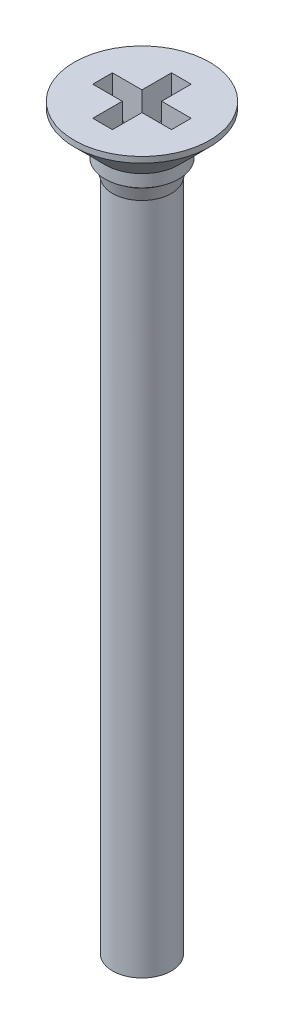
SolidWorks part; units mm, degrees
ref_plane "Vorderseite" through (0, 0, 0) normal (0, 0, 1) x (1, 0, 0)
ref_plane "Oben" through (0, 0, 0) normal (0, 1, 0) x (1, 0, 0)
ref_plane "Rechts" through (0, 0, 0) normal (1, 0, 0) x (0, 0, -1)
sketch "Skizze1" plane through (0, 0, 0) normal (0, 0, 1) x (1, 0, 0)
  line L0 (0, 0) -> (2.75, 0)
  line L1 (2.75, 0) -> (2.75, -0.2375)
  line L2 (2.75, -0.2375) -> (1.5, -1.4875)
  line L3 (1.3375, -1.9875) -> (1.3375, -2.1126)
  line L4 (1.3375, -2.1126) -> (1.1935, -2.65)
  line L5 (1.1935, -2.65) -> (1.1935, -8)
  line L6 (1.1935, -8) -> (0, -8)
  line L7 (0, 0) -> (0, -8) construction
  line L8 (0, 0) -> (0, -8)
  line L10 (1.5, -1.4875) -> (1.5, -1.9875)
  line L12 (1.5, -1.9875) -> (1.3375, -1.9875)
  point P3 (1.3375, -1.65)
  dimension "D1" = 45
  dimension "D2" = 15
  dimension "K" = 1.65
  dimension "DA" = 5.5
  dimension "DK" = 2.387
  dimension "L" = 8
  dimension "DG" = 3
  dimension "A" = 1
  dimension "DF" = 2.675
  dimension "P" = 0.5
revolve "Basis-Rotation" add sketch "Skizze1" angle 360 about L7
sketch "Skizze2" plane through (0, 0, 0) normal (0, 0, 1) x (1, 0, 0)
  line L0 (0, -2.1) -> (0, 0) construction
  line L1 (0, 0) -> (0, -8) construction
  line L2 (-0.55, -2.1) -> (0.55, -2.1)
  line L3 (1.6, 0) -> (1.6, -1.05)
  line L4 (1.6, -1.05) -> (0.55, -2.1)
  line L5 (1.6, 0) -> (-1.6, 0)
  line L6 (-1.6, -1.05) -> (-0.55, -2.1)
  line L7 (-1.6, 0) -> (-1.6, -1.05)
  line L8 (0, -1.05) -> (1.6, -1.05) construction
  line L9 (2.75, 0) -> (-2.75, 0) construction
  line L11 (1.5, -1.4875) -> (2.75, -0.2375) construction
  point P11 (0, 0)
  dimension "M" = 3.2
  dimension "T" = 2.1
extrude "Kreuzschlitz1 H" cut sketch "Skizze2" against normal blind 0.4 and the other way blind 0.4
sketch "Skizze3" plane through (0, 0, 0) normal (1, 0, 0) x (0, 0, -1)
  line L0 (0, -2.1) -> (0, 0) construction
  line L2 (-0.55, -2.1) -> (0.55, -2.1)
  line L3 (1.6, 0) -> (1.6, -1.05)
  line L4 (1.6, -1.05) -> (0.55, -2.1)
  line L5 (1.6, 0) -> (-1.6, 0)
  line L6 (-1.6, -1.05) -> (-0.55, -2.1)
  line L7 (-1.6, 0) -> (-1.6, -1.05)
  line L8 (0, -1.05) -> (1.6, -1.05) construction
  point P11 (0, 0)
extrude "Kreuzschlitz2 H" cut sketch "Skizze3" against normal blind 0.4 and the other way blind 0.4
sketch "Skizze4" plane through (2.4522, 0, -1.8507) normal (0, 1, 0) x (-1, 0, 0)
  line L0 (7.3522, 1.8507) -> (-2.4478, 1.8507) construction
  line L1 (2.4522, -3.0493) -> (2.4522, 6.7507) construction
  line L2 (-2.4478, 1.0342) -> (-2.4478, 2.6672)
  line L3 (-2.4478, 1.0342) -> (0.0059, 1.0342)
  line L4 (0.0059, 1.0342) -> (0.8191, 0.6258)
  line L5 (1.2273, 0.2176) -> (-1.0126, -1.6141)
  line L6 (0.8191, 0.6258) -> (-1.0126, -1.6141)
  line L7 (1.6357, -0.5956) -> (1.2273, 0.2176)
  line L8 (1.6357, -3.0493) -> (1.6357, -0.5956)
  line L9 (1.6357, -3.0493) -> (3.2687, -3.0493)
  line L10 (3.2687, -3.0493) -> (3.2687, -0.5956)
  line L11 (3.2687, -0.5956) -> (3.6772, 0.2176)
  line L12 (2.4522, 1.8507) -> (-1.0126, -1.6141) construction
  line L13 (4.0854, 0.6258) -> (5.917, -1.6141)
  line L14 (3.6772, 0.2176) -> (5.917, -1.6141)
  line L15 (4.8986, 1.0342) -> (4.0854, 0.6258)
  line L16 (7.3522, 1.0342) -> (4.8986, 1.0342)
  line L17 (7.3522, 1.0342) -> (7.3522, 2.6672)
  line L18 (7.3522, 2.6672) -> (4.8986, 2.6672)
  line L19 (4.8986, 2.6672) -> (4.0854, 3.0757)
  line L20 (3.6772, 3.4839) -> (5.917, 5.3156)
  line L21 (4.0854, 3.0757) -> (5.917, 5.3156)
  line L22 (3.2687, 4.2971) -> (3.6772, 3.4839)
  line L23 (3.2687, 6.7507) -> (3.2687, 4.2971)
  line L24 (1.6357, 6.7507) -> (3.2687, 6.7507)
  line L25 (1.6357, 6.7507) -> (1.6357, 4.2971)
  line L26 (1.6357, 4.2971) -> (1.2273, 3.4839)
  line L27 (0.8191, 3.0757) -> (-1.0126, 5.3156)
  line L28 (1.2273, 3.4839) -> (-1.0126, 5.3156)
  line L29 (0.0059, 2.6672) -> (0.8191, 3.0757)
  line L30 (-2.4478, 2.6672) -> (0.0059, 2.6672)
  circle A0 centre (2.4522, 1.8507) radius 4.9 construction
  circle A1 centre (2.4522, 1.8507) radius 2.0415 construction
  circle A2 centre (2.4522, 1.8507) radius 2.579 construction
  dimension "X2" = 4.083
  dimension "X1" = 5.158
  dimension "M" = 9.8
  dimension "D3" = 5.725
  dimension "X3" = 1.633
sketch "Sketch1" plane through (0, -8, 0) normal (0, -1, 0) x (1, 0, 0)
  circle A0 centre (0, 0) radius 1.1935
extrude "Boss-Extrude1" add sketch "Sketch1" along normal blind 22
